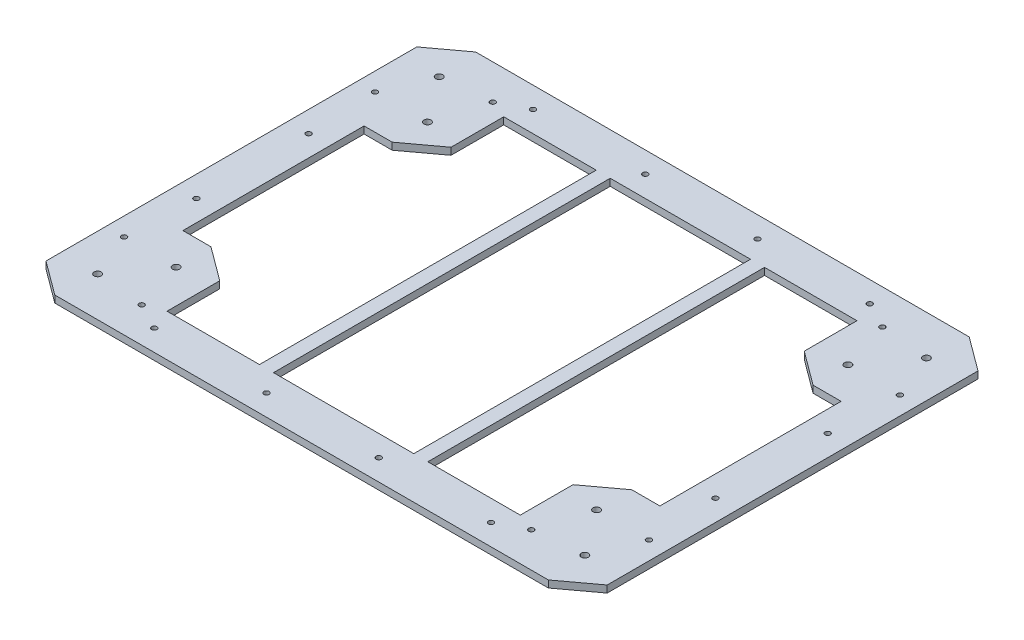
SolidWorks part; units mm, degrees
material "Thornel Mat VMA"
ref_plane "Front Plane" through (0, 0, 0) normal (0, 0, 1) x (1, 0, 0)
ref_plane "Top Plane" through (0, 0, 0) normal (0, 1, 0) x (1, 0, 0)
ref_plane "Right Plane" through (0, 0, 0) normal (1, 0, 0) x (0, 0, -1)
sketch "Sketch1" plane through (0, 0, 0) normal (0, 1, 0) x (1, 0, 0)
  line L0 (-127, 83.9186) -> (-111.6865, 95.25)
  line L1 (-127, -95.25) -> (127, -95.25)
  line L2 (-127, -95.25) -> (-127, 95.25)
  line L3 (-127, 95.25) -> (127, 95.25)
  line L4 (127, -95.25) -> (127, 95.25)
  line L5 (-107.95, 41.011) -> (-107.95, -41.011)
  line L7 (-38.1, -76.2) -> (-38.1, 76.2)
  line L8 (-107.95, 41.011) -> (-95.25, 41.011)
  line L9 (-31.75, -76.2) -> (-31.75, 76.2)
  line L10 (-127, 95.25) -> (127, -95.25) construction
  line L12 (127, 83.9186) -> (111.6865, 95.25)
  line L13 (38.1, -76.2) -> (38.1, 76.2)
  line L14 (79.9365, 52.3423) -> (79.9365, 76.2)
  line L15 (95.25, 41.011) -> (79.9365, 52.3423)
  line L16 (107.95, 41.011) -> (95.25, 41.011)
  line L17 (107.95, 41.011) -> (107.95, -41.011)
  line L18 (127, -83.9186) -> (111.6865, -95.25)
  line L19 (107.95, -41.011) -> (95.25, -41.011)
  line L20 (95.25, -41.011) -> (79.9365, -52.3423)
  line L21 (79.9365, -52.3423) -> (79.9365, -76.2)
  line L22 (127, 0) -> (-127, 0) construction
  line L23 (0, -13.6985) -> (0, 95.25) construction
  line L25 (-79.9365, -76.2) -> (-38.1, -76.2)
  line L26 (-79.9365, -52.3423) -> (-79.9365, -76.2)
  line L27 (-95.25, 41.011) -> (-127, 83.9186) construction
  line L28 (-95.25, 41.011) -> (-79.9365, 52.3423)
  line L29 (-79.9365, 52.3423) -> (-79.9365, 76.2)
  line L30 (-79.9365, 76.2) -> (-38.1, 76.2)
  line L31 (-95.25, -41.011) -> (-79.9365, -52.3423)
  line L32 (-107.95, -41.011) -> (-95.25, -41.011)
  line L33 (-127, -83.9186) -> (-111.6865, -95.25)
  line L34 (-79.9365, 52.3423) -> (-111.6865, 95.25) construction
  line L35 (31.75, -76.2) -> (31.75, 76.2)
  line L36 (-31.75, 76.2) -> (31.75, 76.2)
  line L37 (38.1, 76.2) -> (79.9365, 76.2)
  line L38 (-31.75, -76.2) -> (31.75, -76.2)
  line L39 (38.1, -76.2) -> (79.9365, -76.2)
  point P0 (0, 0)
  point P1 (0, 0)
  point P14 (0, 0)
  point P22 (0, 76.2)
  point P33 (107.95, 0)
  point P41 (0, 0)
  point P44 (-107.95, 0)
  point P45 (-38.1, 0)
  point P46 (-31.75, 0)
  dimension "D1" = 190.5
  dimension "D2" = 254
  dimension "D3" = 19.05
  dimension "D4" = 19.05
  dimension "D9" = 31.75
  dimension "D5" = 143.5
  dimension "D6" = 19.05
  dimension "D7" = 12.7
  dimension "D8" = 6.35
extrude "Boss-Extrude1" add sketch "Sketch1" along normal blind 3.175
sketch "Sketch2" plane through (0, 3.175, 0) normal (0, 1, 0) x (1, 0, 0)
  line L0 (-87.5933, 46.6767) -> (-119.3433, 89.5843) construction
  line L1 (-95.25, 41.011) -> (-79.9365, 52.3423) construction
  line L2 (-127, 83.9186) -> (-111.6865, 95.25) construction
  line L3 (0, 0) -> (0, 95.25) construction
  line L4 (-111.6865, 95.25) -> (111.6865, 95.25) construction
  line L5 (0, 0) -> (-127, 0) construction
  line L6 (-127, -83.9186) -> (-127, 83.9186) construction
  line L7 (-103.4683, 68.1305) -> (-88.1548, 79.4619) construction
  circle A0 centre (-95.1475, 56.8856) radius 1.5875
  circle A1 centre (-110.256, 77.3036) radius 1.5875
  circle A2 centre (110.256, 77.3036) radius 1.5875
  circle A3 centre (95.1475, 56.8856) radius 1.5875
  circle A4 centre (110.256, -77.3036) radius 1.5875
  circle A5 centre (95.1475, -56.8856) radius 1.5875
  circle A6 centre (-110.256, -77.3036) radius 1.5875
  circle A7 centre (-95.1475, -56.8856) radius 1.5875
  circle A8 centre (-88.1548, 79.4619) radius 1.1906
  circle A9 centre (-118.7817, 56.7991) radius 1.1906
  circle A10 centre (118.7817, 56.7991) radius 1.1906
  circle A11 centre (88.1548, 79.4619) radius 1.1906
  circle A12 centre (118.7817, -56.7991) radius 1.1906
  circle A13 centre (88.1548, -79.4619) radius 1.1906
  circle A14 centre (-88.1548, -79.4619) radius 1.1906
  circle A15 centre (-118.7817, -56.7991) radius 1.1906
  dimension "D2" = 3.175
  dimension "D3" = 3.175
  dimension "D5" = 2.3813
  dimension "D1" = 25.4
  dimension "D4" = 12.7
  dimension "D6" = 19.05
extrude "Cut-Extrude1" cut sketch "Sketch2" against normal through all
sketch "Sketch3" plane through (0, 3.175, 0) normal (0, 1, 0) x (1, 0, 0)
  line L0 (-79.9365, 76.2) -> (-79.9365, 95.25) construction
  line L1 (-111.6865, 95.25) -> (111.6865, 95.25) construction
  line L2 (-79.9365, 85.725) -> (79.9365, 85.725) construction
  line L3 (79.9365, 76.2) -> (79.9365, 95.25) construction
  line L4 (0, 0) -> (76.2, 0) construction
  line L5 (-107.95, -41.011) -> (-127, -41.011) construction
  line L6 (-127, -83.9186) -> (-127, 83.9186) construction
  line L7 (-107.95, 41.011) -> (-127, 41.011) construction
  line L8 (-117.475, 41.011) -> (-117.475, -41.011) construction
  line L9 (0, 0) -> (0, 36.2879) construction
  circle A0 centre (-76.2, 85.725) radius 1.1906
  circle A1 centre (-25.4, 85.725) radius 1.1906
  circle A2 centre (25.4, 85.725) radius 1.1906
  circle A3 centre (76.2, 85.725) radius 1.1906
  circle A4 centre (76.2, -85.725) radius 1.1906
  circle A5 centre (25.4, -85.725) radius 1.1906
  circle A6 centre (-25.4, -85.725) radius 1.1906
  circle A7 centre (-76.2, -85.725) radius 1.1906
  circle A8 centre (-117.475, -25.4) radius 1.1906
  circle A9 centre (-117.475, 25.4) radius 1.1906
  circle A10 centre (117.475, 25.4) radius 1.1906
  circle A11 centre (117.475, -25.4) radius 1.1906
  point P12 (0, 85.725)
  point P40 (-117.475, 0)
  dimension "D1" = 2.3813
  dimension "D2" = 76.2
  dimension "D4" = 2.3813
  dimension "D5" = 25.4
  dimension "D3" = 4
  dimension "D6" = 2
extrude "Cut-Extrude2" cut sketch "Sketch3" against normal through all
